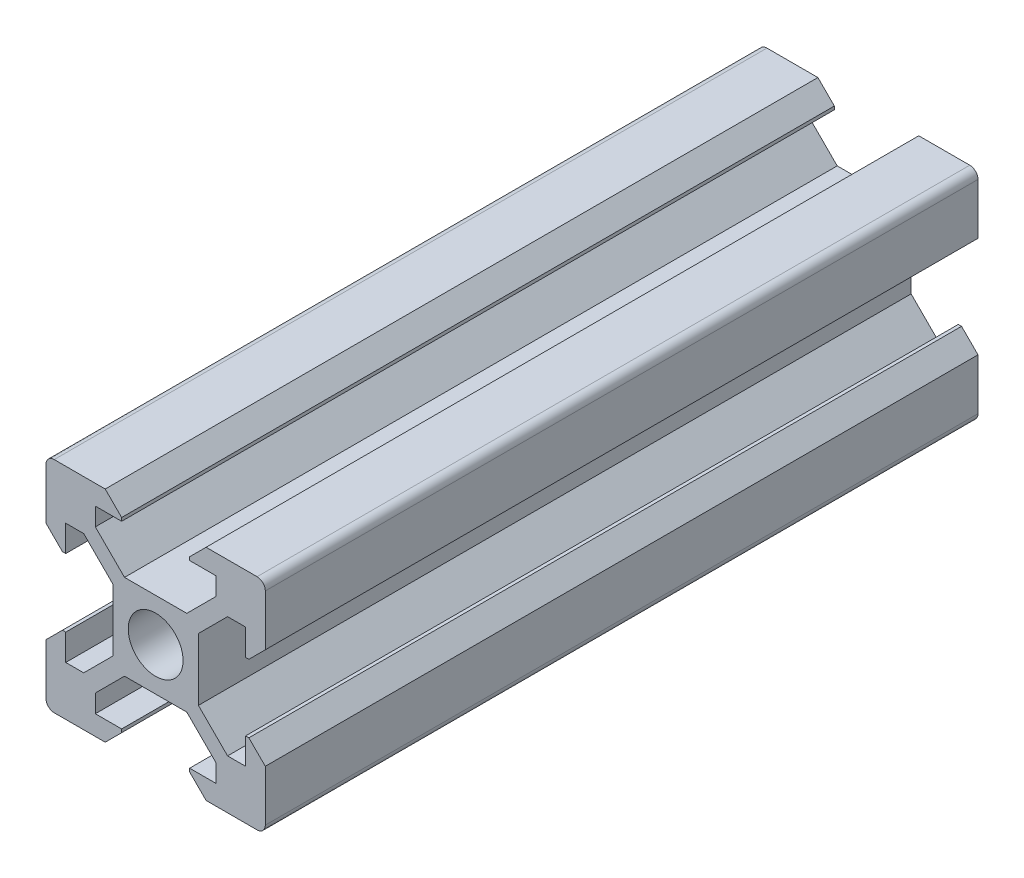
SolidWorks part; units mm, degrees
other "Markup1"
sketch "Sketch1" plane through (10, 10, 480) normal (0.5774, 0.5773, 0.5774) x (0.7071, 0, -0.7071)
ref_plane "Alzado" through (0, 0, 0) normal (0, 0, 1) x (1, 0, 0)
ref_plane "Planta" through (0, 0, 0) normal (0, 1, 0) x (1, 0, 0)
ref_plane "Vista lateral" through (0, 0, 0) normal (1, 0, 0) x (0, 0, -1)
sketch "Croquis1" plane through (0, 0, 0) normal (0, 0, 1) x (1, 0, 0)
  line L0 (-4.6, 10) -> (-3.1, 8.5)
  line L3 (-4.6, 10) -> (-9.25, 10)
  line L5 (-3.1, 8.5) -> (-3.1, 8.2)
  line L6 (-3.1, 8.2) -> (-5.5, 8.2)
  line L7 (-5.5, 8.2) -> (-5.5, 6.5607)
  line L8 (-5.5, 6.5607) -> (-2.84, 3.9007)
  line L9 (-2.84, 3.9007) -> (0, 3.9007)
  line L10 (0, 0) -> (-15.3499, 15.3499) construction
  line L11 (-3.9007, 2.84) -> (-3.9007, 0)
  line L12 (-6.5607, 5.5) -> (-3.9007, 2.84)
  line L13 (-8.2, 5.5) -> (-6.5607, 5.5)
  line L14 (-8.2, 3.1) -> (-8.2, 5.5)
  line L15 (-8.5, 3.1) -> (-8.2, 3.1)
  line L16 (-10, 4.6) -> (-10, 9.25)
  line L17 (-10, 4.6) -> (-8.5, 3.1)
  line L18 (10, 4.6) -> (8.5, 3.1)
  line L19 (10, 4.6) -> (10, 9.25)
  line L20 (8.5, 3.1) -> (8.2, 3.1)
  line L21 (8.2, 3.1) -> (8.2, 5.5)
  line L22 (8.2, 5.5) -> (6.5607, 5.5)
  line L23 (6.5607, 5.5) -> (3.9007, 2.84)
  line L24 (3.9007, 2.84) -> (3.9007, 0)
  line L25 (5.5, 6.5607) -> (2.84, 3.9007)
  line L26 (5.5, 8.2) -> (5.5, 6.5607)
  line L27 (3.1, 8.2) -> (5.5, 8.2)
  line L28 (3.1, 8.5) -> (3.1, 8.2)
  line L29 (4.6, 10) -> (9.25, 10)
  line L30 (4.6, 10) -> (3.1, 8.5)
  line L31 (2.84, 3.9007) -> (0, 3.9007)
  line L32 (4.6, -10) -> (3.1, -8.5)
  line L33 (4.6, -10) -> (9.25, -10)
  line L34 (3.1, -8.5) -> (3.1, -8.2)
  line L35 (3.1, -8.2) -> (5.5, -8.2)
  line L36 (5.5, -8.2) -> (5.5, -6.5607)
  line L37 (5.5, -6.5607) -> (2.84, -3.9007)
  line L38 (2.84, -3.9007) -> (0, -3.9007)
  line L39 (6.5607, -5.5) -> (3.9007, -2.84)
  line L40 (8.2, -5.5) -> (6.5607, -5.5)
  line L41 (8.2, -3.1) -> (8.2, -5.5)
  line L42 (8.5, -3.1) -> (8.2, -3.1)
  line L43 (10, -4.6) -> (10, -9.25)
  line L44 (10, -4.6) -> (8.5, -3.1)
  line L45 (3.9007, -2.84) -> (3.9007, 0)
  line L46 (-10, -4.6) -> (-8.5, -3.1)
  line L47 (-10, -4.6) -> (-10, -9.25)
  line L48 (-8.5, -3.1) -> (-8.2, -3.1)
  line L49 (-8.2, -3.1) -> (-8.2, -5.5)
  line L50 (-8.2, -5.5) -> (-6.5607, -5.5)
  line L51 (-6.5607, -5.5) -> (-3.9007, -2.84)
  line L52 (-3.9007, -2.84) -> (-3.9007, 0)
  line L53 (-5.5, -6.5607) -> (-2.84, -3.9007)
  line L54 (-5.5, -8.2) -> (-5.5, -6.5607)
  line L55 (-3.1, -8.2) -> (-5.5, -8.2)
  line L56 (-3.1, -8.5) -> (-3.1, -8.2)
  line L57 (-4.6, -10) -> (-9.25, -10)
  line L58 (-4.6, -10) -> (-3.1, -8.5)
  line L59 (-2.84, -3.9007) -> (0, -3.9007)
  circle A0 centre (0, 0) radius 2.5
  arc A1 (-9.25, 10) -> (-10, 9.25) centre (-9.25, 9.25) ccw
  arc A2 (10, 9.25) -> (9.25, 10) centre (9.25, 9.25) ccw
  arc A3 (9.25, -10) -> (10, -9.25) centre (9.25, -9.25) ccw
  arc A4 (-10, -9.25) -> (-9.25, -10) centre (-9.25, -9.25) ccw
  point P18 (-10, 10)
  point P37 (10, 10)
  point P55 (10, -10)
  point P73 (-10, -10)
  point P79 (0, 0)
  dimension "D1" = 5
  dimension "D5" = 0.75
  dimension "D2" = 10
  dimension "D3" = 10
  dimension "D4" = 4.6
  dimension "D6" = 5.5
  dimension "D7" = 135
  dimension "D8" = 0.75
  dimension "D9" = 225
  dimension "D10" = 2.84
  dimension "D11" = 1.8
  dimension "D12" = 3.1
  dimension "D13" = 4
extrude "Saliente-Extruir1" add sketch "Croquis1" along normal blind 480
sketch "Sketch2" plane through (0, 0, 0) normal (1, 0, 0) x (0, 0, -1)
  line L0 (-415, 49.0269) -> (-415, -60.8966) construction
  line L1 (-415, -18.6697) -> (415, -18.6697)
  line L2 (-415, -18.6697) -> (-415, 18.6697)
  line L3 (-415, 18.6697) -> (415, 18.6697)
  line L4 (415, -18.6697) -> (415, 18.6697)
  line L5 (-415, -18.6697) -> (415, 18.6697) construction
  line L6 (-415, 18.6697) -> (415, -18.6697) construction
  line L7 (-480, -2.84) -> (-480, 2.84) construction
  point P0 (0, 0)
  dimension "D1" = 65
extrude "Cut-Extrude1" cut sketch "Sketch2" against normal blind 46 and the other way blind 47 contours L2 L1 L4 L3
